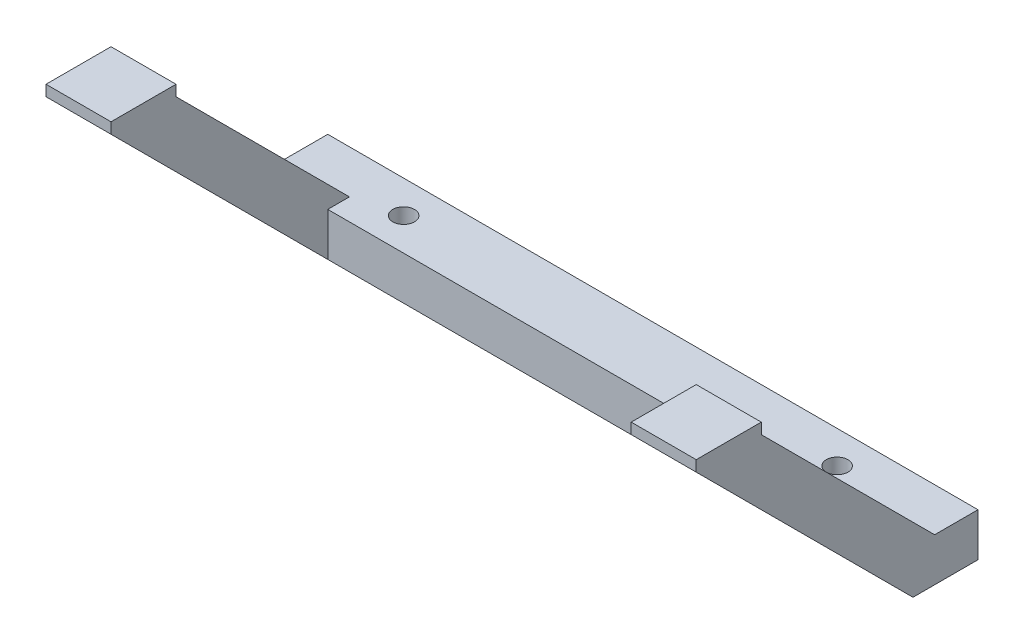
SolidWorks part; units mm, degrees
ref_plane "Front Plane" through (0, 0, 0) normal (0, 0, 1) x (1, 0, 0)
ref_plane "Top Plane" through (0, 0, 0) normal (0, 1, 0) x (1, 0, 0)
ref_plane "Right Plane" through (0, 0, 0) normal (1, 0, 0) x (0, 0, -1)
sketch "Sketch1" plane through (0, 0, 0) normal (0, 1, 0) x (1, 0, 0)
  line L1 (-12, 1.5) -> (12, 1.5)
  line L2 (-12, 1.5) -> (-12, -1.5)
  line L3 (-12, -1.5) -> (12, -1.5)
  line L4 (12, 1.5) -> (12, -1.5)
  point P0 (0, 0)
  dimension "D1" = 3
  dimension "D2" = 24
  dimension "D3" = 12
extrude "Boss-Extrude1" add sketch "Sketch1" along normal blind 2
sketch "Sketch4" plane through (12, 0, 0) normal (1, 0, 0) x (0, 0, -1)
  line L2 (-11.5, 10) -> (-1.5, 0)
  line L6 (-11.5, 10) -> (-8.5, 10)
  line L7 (-8.5, 10) -> (-0.5, 2)
  line L8 (1.5, 0) -> (-1.5, 0)
  line L9 (1.5, 0) -> (1.5, 2)
  line L10 (1.5, 2) -> (-0.5, 2)
  line L11 (-1.5, 2) -> (1.5, 2) construction
extrude "Boss-Extrude2" add sketch "Sketch4" along normal blind 3
sketch "Sketch5" plane through (-12, 0, 0) normal (-1, 0, 0) x (0, 0, 1)
  line L0 (1.5, 0) -> (11.5, 10)
  line L1 (11.5, 10) -> (8.5, 10)
  line L2 (8.5, 10) -> (0.5, 2)
  line L3 (0.5, 2) -> (-1.5, 2)
  line L4 (-1.5, 2) -> (-1.5, 0)
  line L5 (-1.5, 0) -> (1.5, 0)
extrude "Boss-Extrude3" add sketch "Sketch5" along normal blind 3
sketch "Sketch6" plane through (0, 0, 0) normal (0, -1, 0) x (1, 0, 0)
  circle A0 centre (-10, 0) radius 0.5
  circle A1 centre (10, 0) radius 0.5
  dimension "D1" = 1
  dimension "D2" = 1
extrude "Cut-Extrude1" cut sketch "Sketch6" against normal up to next
sketch "Sketch9" plane through (0, 10, 0) normal (0, 1, 0) x (1, 0, 0)
  line L1 (-15, -8.5) -> (-12, -8.5)
  line L2 (-15, -8.5) -> (-15, -11.5)
  line L3 (-15, -11.5) -> (-12, -11.5)
  line L4 (-12, -8.5) -> (-12, -11.5)
  line L5 (-15, -8.5) -> (-12, -11.5) construction
  line L6 (-15, -11.5) -> (-12, -8.5) construction
  line L7 (12, -8.5) -> (15, -8.5)
  line L8 (12, -8.5) -> (12, -11.5)
  line L9 (12, -11.5) -> (15, -11.5)
  line L10 (15, -8.5) -> (15, -11.5)
  line L11 (12, -8.5) -> (15, -11.5) construction
  line L12 (12, -11.5) -> (15, -8.5) construction
  point P0 (-13.5, -10)
  point P5 (13.5, -10)
extrude "Boss-Extrude4" add sketch "Sketch9" along normal blind 0.5
